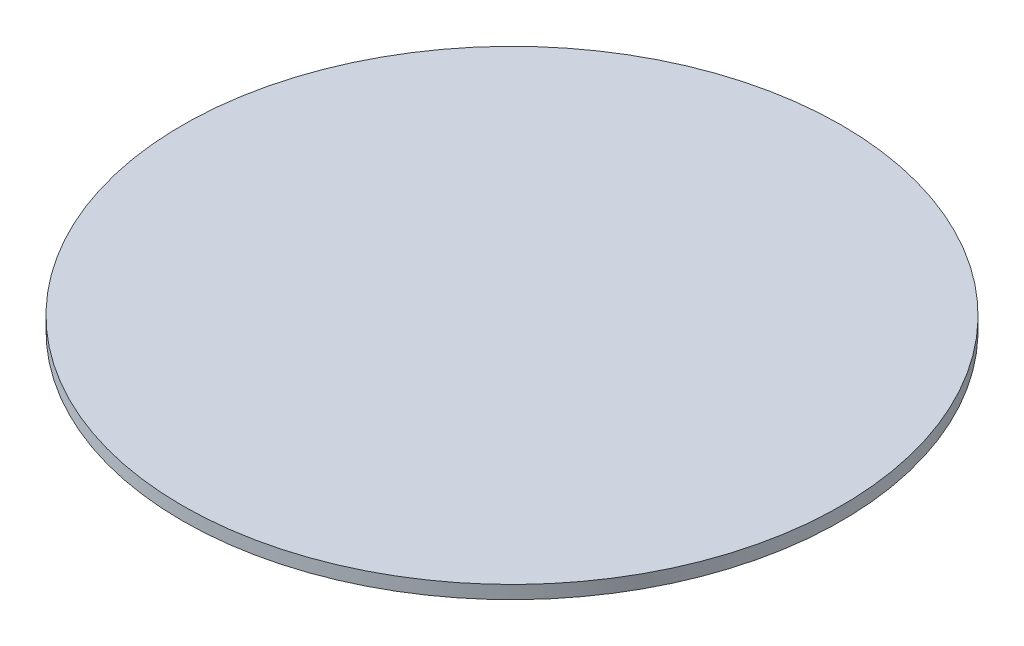
SolidWorks part; units mm, degrees
ref_plane "Front Plane" through (0, 0, 0) normal (0, 0, 1) x (1, 0, 0)
ref_plane "Top Plane" through (0, 0, 0) normal (0, 1, 0) x (1, 0, 0)
ref_plane "Right Plane" through (0, 0, 0) normal (1, 0, 0) x (0, 0, -1)
sketch "Sketch1" plane through (0, 0, 0) normal (0, 1, 0) x (1, 0, 0)
  circle A0 centre (0, 0) radius 75
extrude "Boss-Extrude2" add sketch "Sketch1" along normal blind 3 contours A0
